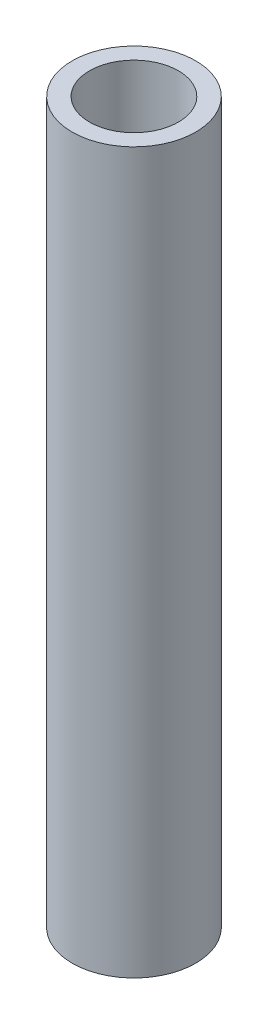
SolidWorks part; units mm, degrees
material "AISI 316 Stainless Steel Sheet (SS)"
ref_plane "Front Plane" through (0, 0, 0) normal (0, 0, 1) x (1, 0, 0)
ref_plane "Top Plane" through (0, 0, 0) normal (0, 1, 0) x (1, 0, 0)
ref_plane "Right Plane" through (0, 0, 0) normal (1, 0, 0) x (0, 0, -1)
sketch "Sketch1" plane through (0, 0, 0) normal (0, 1, 0) x (1, 0, 0)
  circle A0 centre (0, 0) radius 3.175
  circle A1 centre (0, 0) radius 2.286
  dimension "D1" = 6.35
  dimension "D2" = 0.889
extrude "Boss-Extrude1" add sketch "Sketch1" along normal blind 37
